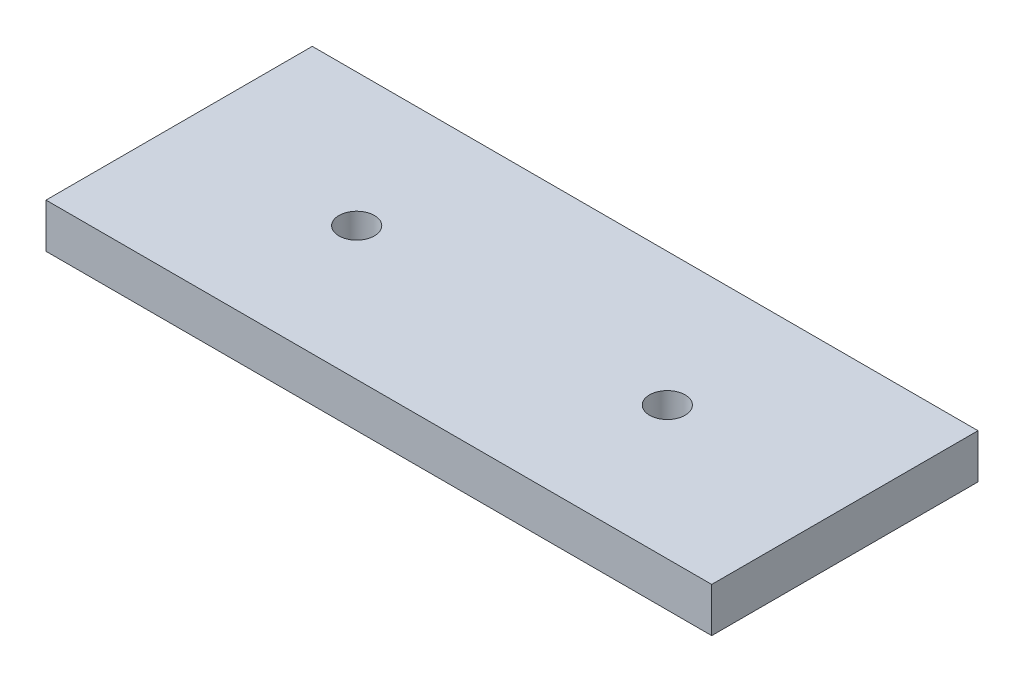
SolidWorks part; units mm, degrees
ref_plane "Front Plane" through (0, 0, 0) normal (0, 0, 1) x (1, 0, 0)
ref_plane "Top Plane" through (0, 0, 0) normal (0, 1, 0) x (1, 0, 0)
ref_plane "Right Plane" through (0, 0, 0) normal (1, 0, 0) x (0, 0, -1)
sketch "Sketch1" plane through (0, 0, 0) normal (0, 1, 0) x (1, 0, 0)
  line L0 (0, -15) -> (75, -15) construction
  line L1 (0, 0) -> (75, 0)
  line L2 (0, 0) -> (0, -30)
  line L3 (0, -30) -> (75, -30)
  line L4 (75, 0) -> (75, -30)
  line L5 (55, -15) -> (20, -15) construction
  circle A0 centre (20, -15) radius 2
  circle A1 centre (55, -15) radius 2
  point P10 (37.5, -15)
  dimension "D4" = 4
  dimension "D1" = 75
  dimension "D2" = 30
  dimension "D3" = 20
extrude "Boss-Extrude1" add sketch "Sketch1" along normal blind 5
